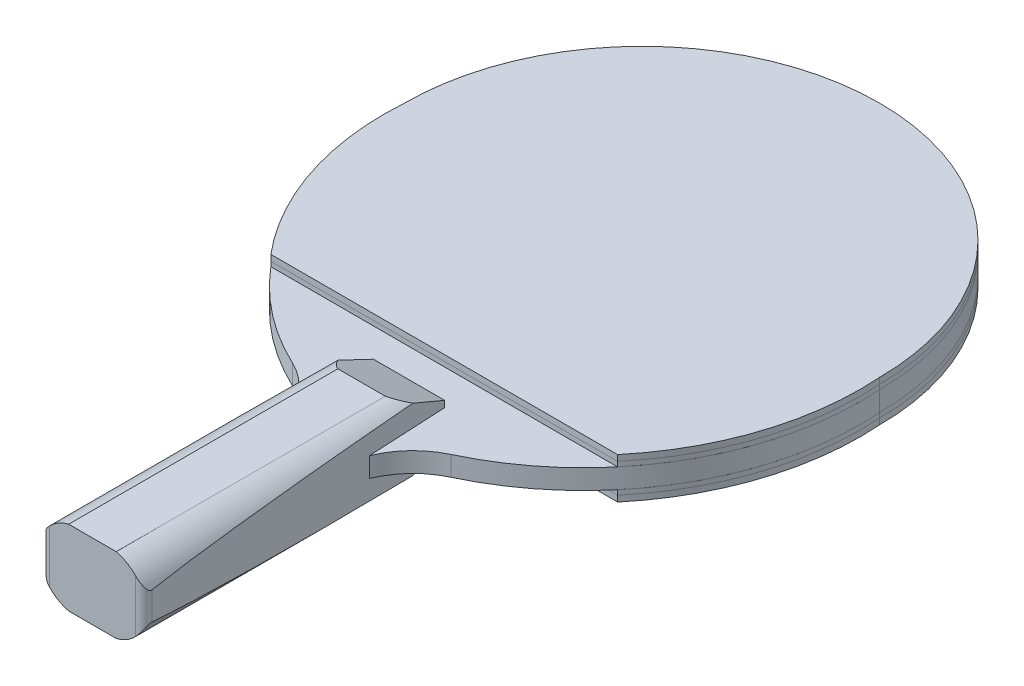
SolidWorks part; units mm, degrees
material "Beech"
ref_plane "Front Plane" through (0, 0, 0) normal (0, 0, 1) x (1, 0, 0)
ref_plane "Top Plane" through (0, 0, 0) normal (0, 1, 0) x (1, 0, 0)
ref_plane "Right Plane" through (0, 0, 0) normal (1, 0, 0) x (0, 0, -1)
sketch "Sketch2" plane through (0, 0, 0) normal (0, 1, 0) x (1, 0, 0)
  line L0 (0, -1000) -> (0, 49000) construction
  line L1 (-12.7, -100.1709) -> (-16.3767, -173.7041)
  line L2 (-13.8398, -176.3709) -> (13.8398, -176.3709)
  line L3 (12.7, -100.1709) -> (16.3767, -173.7041)
  arc A0 (-76.2, 0) -> (76.2, 0) centre (0, 0) cw
  arc A1 (76.2, 0) -> (25.4, -86.7792) centre (-12.4729, -6.35) cw
  arc A2 (-76.2, 0) -> (-25.4, -86.7792) centre (12.4729, -6.35) ccw
  arc A3 (25.4, -86.7792) -> (12.7, -100.1709) centre (36.2208, -109.7589) ccw
  arc A4 (-25.4, -86.7792) -> (-12.7, -100.1709) centre (-36.2208, -109.7589) cw
  arc A5 (-16.3767, -173.7041) -> (-13.8398, -176.3709) centre (-13.8398, -173.8309) ccw
  arc A6 (16.3767, -173.7041) -> (13.8398, -176.3709) centre (13.8398, -173.8309) cw
  point P17 (0, -176.3709)
  point P19 (-16.51, -176.3709)
  point P22 (16.51, -176.3709)
  dimension "D1" = 76.2
  dimension "D3" = 88.9
  dimension "D6" = 25.4
  dimension "D9" = 2.54
  dimension "D2" = 50.8
  dimension "D4" = 6.35
  dimension "D5" = 25.4
  dimension "D7" = 76.2
  dimension "D8" = 16.51
extrude "Boss-Extrude1" add sketch "Sketch2" along normal blind 6.35
sketch "Sketch3" plane through (0, 6.35, 0) normal (0, 1, 0) x (1, 0, 0)
  line L0 (-55.6232, -63.5) -> (55.6232, -63.5)
  arc A0 (76.2, 0) -> (-76.2, 0) centre (0, 0) ccw construction
  arc A1 (-76.2, 0) -> (-25.4, -86.7792) centre (12.4729, -6.35) ccw construction
  arc A2 (25.4, -86.7792) -> (76.2, 0) centre (-12.4729, -6.35) ccw construction
  arc A3 (76.2, 0) -> (-76.2, 0) centre (0, 0) ccw
  arc A4 (-76.2, 0) -> (-55.6232, -63.5) centre (12.4729, -6.35) ccw
  arc A5 (55.6232, -63.5) -> (76.2, 0) centre (-12.4729, -6.35) ccw
  dimension "D1" = 63.5
extrude "Boss-Extrude2" add sketch "Sketch3" along normal blind 1.524 separate body
sketch "Sketch4" plane through (0, 7.874, 0) normal (0, 1, 0) x (1, 0, 0)
  line L0 (-55.6232, -63.5) -> (55.6232, -63.5) construction
  line L1 (-55.6232, -63.5) -> (55.6232, -63.5)
  arc A0 (-76.2, 0) -> (-55.6232, -63.5) centre (12.4729, -6.35) ccw construction
  arc A1 (76.2, 0) -> (-76.2, 0) centre (0, 0) ccw construction
  arc A2 (55.6232, -63.5) -> (76.2, 0) centre (-12.4729, -6.35) ccw construction
  arc A3 (-76.2, 0) -> (-55.6232, -63.5) centre (12.4729, -6.35) ccw
  arc A4 (76.2, 0) -> (-76.2, 0) centre (0, 0) ccw
  arc A5 (55.6232, -63.5) -> (76.2, 0) centre (-12.4729, -6.35) ccw
extrude "Boss-Extrude4" add sketch "Sketch4" along normal blind 1.905 separate body
ref_plane "Plane1" through (0, 3.175, 0) normal (0, 1, 0) x (1, 0, 0)
sketch "Sketch5" plane through (0, 0, 0) normal (0, -1, 0) x (1, 0, 0)
  line L0 (55.6232, 63.5) -> (-55.6232, 63.5)
  line L3 (12.7, 100.1709) -> (16.3767, 173.7041)
  line L4 (13.8398, 176.3709) -> (-13.8398, 176.3709)
  line L5 (-16.3767, 173.7041) -> (-12.7, 100.1709)
  arc A7 (-25.4, 86.7792) -> (-76.2, 0) centre (12.4729, 6.35) ccw
  arc A8 (-76.2, 0) -> (76.2, 0) centre (0, 0) ccw
  arc A9 (76.2, 0) -> (25.4, 86.7792) centre (-12.4729, 6.35) ccw
  arc A10 (12.7, 100.1709) -> (25.4, 86.7792) centre (36.2208, 109.7589) ccw
  arc A11 (16.3767, 173.7041) -> (13.8398, 176.3709) centre (13.8398, 173.8309) ccw
  arc A12 (-13.8398, 176.3709) -> (-16.3767, 173.7041) centre (-13.8398, 173.8309) ccw
  arc A13 (-25.4, 86.7792) -> (-12.7, 100.1709) centre (-36.2208, 109.7589) ccw
  arc A14 (-55.6232, 63.5) -> (-76.2, 0) centre (12.4729, 6.35) ccw
  arc A15 (-76.2, 0) -> (76.2, 0) centre (0, 0) ccw
  arc A16 (76.2, 0) -> (55.6232, 63.5) centre (-12.4729, 6.35) ccw
  dimension "D2" = 63.5
  dimension "D1" = 0
extrude "Boss-Extrude5" add sketch "Sketch5" along normal blind 1.524 separate body
sketch "Sketch6" plane through (0, -1.524, 0) normal (0, -1, 0) x (1, 0, 0)
  line L1 (55.6232, 63.5) -> (-55.6232, 63.5)
  line L2 (55.6232, 63.5) -> (-55.6232, 63.5)
  arc A3 (76.2, 0) -> (55.6232, 63.5) centre (-12.4729, 6.35) ccw
  arc A4 (-55.6232, 63.5) -> (-76.2, 0) centre (12.4729, 6.35) ccw
  arc A5 (-76.2, 0) -> (76.2, 0) centre (0, 0) ccw
  arc A6 (76.2, 0) -> (55.6232, 63.5) centre (-12.4729, 6.35) ccw
  arc A7 (-55.6232, 63.5) -> (-76.2, 0) centre (12.4729, 6.35) ccw
  arc A8 (-76.2, 0) -> (76.2, 0) centre (0, 0) ccw
  dimension "D1" = 0
extrude "Boss-Extrude6" add sketch "Sketch6" along normal blind 1.905 separate body
sketch "Sketch7" plane through (0, 6.35, 0) normal (0, 1, 0) x (1, 0, 0)
  line L0 (-12.7, -100.1709) -> (-16.3767, -173.7041) construction
  line L1 (16.3767, -173.7041) -> (12.7, -100.1709) construction
  line L2 (-13.8398, -176.3709) -> (13.8398, -176.3709) construction
  line L3 (-11.43, -74.7709) -> (-16.3767, -173.7041)
  line L4 (16.3767, -173.7041) -> (11.43, -74.7709)
  line L5 (-13.8398, -176.3709) -> (13.8398, -176.3709)
  line L6 (-11.43, -74.7709) -> (11.43, -74.7709)
  arc A0 (13.8398, -176.3709) -> (16.3767, -173.7041) centre (13.8398, -173.8309) ccw construction
  arc A1 (-16.3767, -173.7041) -> (-13.8398, -176.3709) centre (-13.8398, -173.8309) ccw construction
  arc A2 (13.8398, -176.3709) -> (16.3767, -173.7041) centre (13.8398, -173.8309) ccw
  arc A3 (-16.3767, -173.7041) -> (-13.8398, -176.3709) centre (-13.8398, -173.8309) ccw
  dimension "D1" = 101.6
extrude "Boss-Extrude7" add sketch "Sketch7" along normal blind 8.89
sketch "Sketch8" plane through (0, 0, 176.3709) normal (0, 0, 1) x (1, 0, 0)
  line L0 (-16.3798, 15.24) -> (-16.3798, 0) construction
  line L1 (-13.8398, 15.24) -> (13.8398, 15.24) construction
  line L2 (16.3798, 0) -> (16.3798, 15.24) construction
  line L4 (0, -1000) -> (0, 15.24) construction
  line L5 (16.3798, 15.24) -> (13.8398, 15.24) construction
  line L6 (-13.8398, 15.24) -> (-16.3798, 15.24) construction
  line L7 (-13.8398, 15.24) -> (-7.62, 15.24)
  line L8 (16.3798, 15.24) -> (13.8398, 15.24)
  line L9 (16.3798, 7.62) -> (16.3798, 15.24)
  line L10 (-13.8398, 15.24) -> (-16.3798, 15.24)
  line L11 (-16.3798, 15.24) -> (-16.3798, 7.62)
  line L12 (7.62, 15.24) -> (13.8398, 15.24)
  arc A0 (-16.3798, 7.62) -> (-7.62, 15.24) centre (-4.5865, 2.9076) cw
  arc A1 (16.3798, 7.62) -> (7.62, 15.24) centre (4.5865, 2.9076) ccw
  dimension "D2" = 12.7
  dimension "D3" = 12.7
  dimension "D1" = 15.24
extrude "Cut-Extrude1" cut sketch "Sketch8" against normal blind 101.6
sketch "Sketch9" plane through (0, 0, -0.1919) normal (1, 0, 0) x (0, 0, -1)
  line L0 (-74.9628, 8.382) -> (-90.2028, 15.24)
  line L1 (-74.9628, 13.606) -> (-74.9628, 6.35) construction
  line L2 (-74.9628, 15.24) -> (-176.5628, 15.24) construction
  line L3 (-90.2028, 15.24) -> (-74.9628, 15.24)
  line L4 (-74.9628, 15.24) -> (-74.9628, 8.382)
  dimension "D1" = 15.24
  dimension "D2" = 15.24
  dimension "D3" = 6.858
extrude "Cut-Extrude2" cut sketch "Sketch9" against normal mid plane 50.8
mirror "Mirror8" about plane through (0, 3.175, 0) normal (0, 1, 0) of "Cut-Extrude2", "Cut-Extrude1", "Boss-Extrude7"
